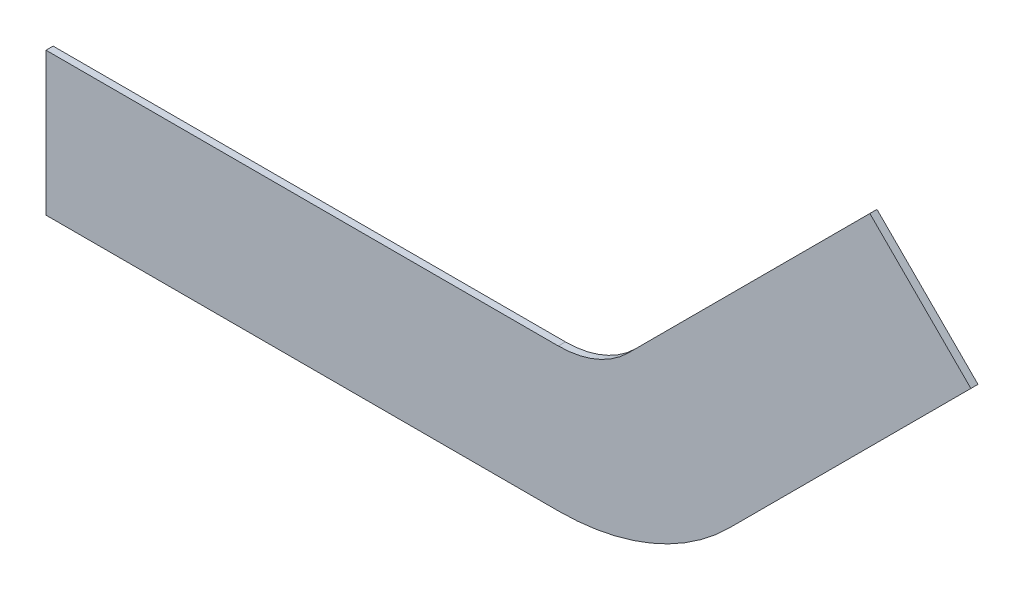
SolidWorks part; units mm, degrees
ref_plane "Front Plane" through (0, 0, 0) normal (0, 0, 1) x (1, 0, 0)
ref_plane "Top Plane" through (0, 0, 0) normal (0, 1, 0) x (1, 0, 0)
ref_plane "Right Plane" through (0, 0, 0) normal (1, 0, 0) x (0, 0, -1)
sketch "Sketch1" plane through (0, 0, 0) normal (0, 0, 1) x (1, 0, 0)
  line L0 (0, 0) -> (0, -63.754)
  line L1 (0, -63.754) -> (228.6, -63.754)
  line L2 (304.9322, -32.1362) -> (412.6953, 75.6269)
  line L3 (0, 0) -> (228.6, 0)
  line L4 (259.8513, 12.9447) -> (367.6144, 120.7078)
  line L5 (412.6953, 75.6269) -> (367.6144, 120.7078)
  arc A0 (228.6, -63.754) -> (304.9322, -32.1362) centre (228.6, 44.196) ccw
  arc A1 (228.6, 0) -> (259.8513, 12.9447) centre (228.6, 44.196) ccw
  point P8 (370.0069, 120.4775)
  dimension "D1" = 107.95
  dimension "D2" = 45
  dimension "D3" = 228.6
  dimension "D4" = 152.4
  dimension "D5" = 63.754
extrude "Base Extrude" add sketch "Sketch1" along normal blind 3.175
